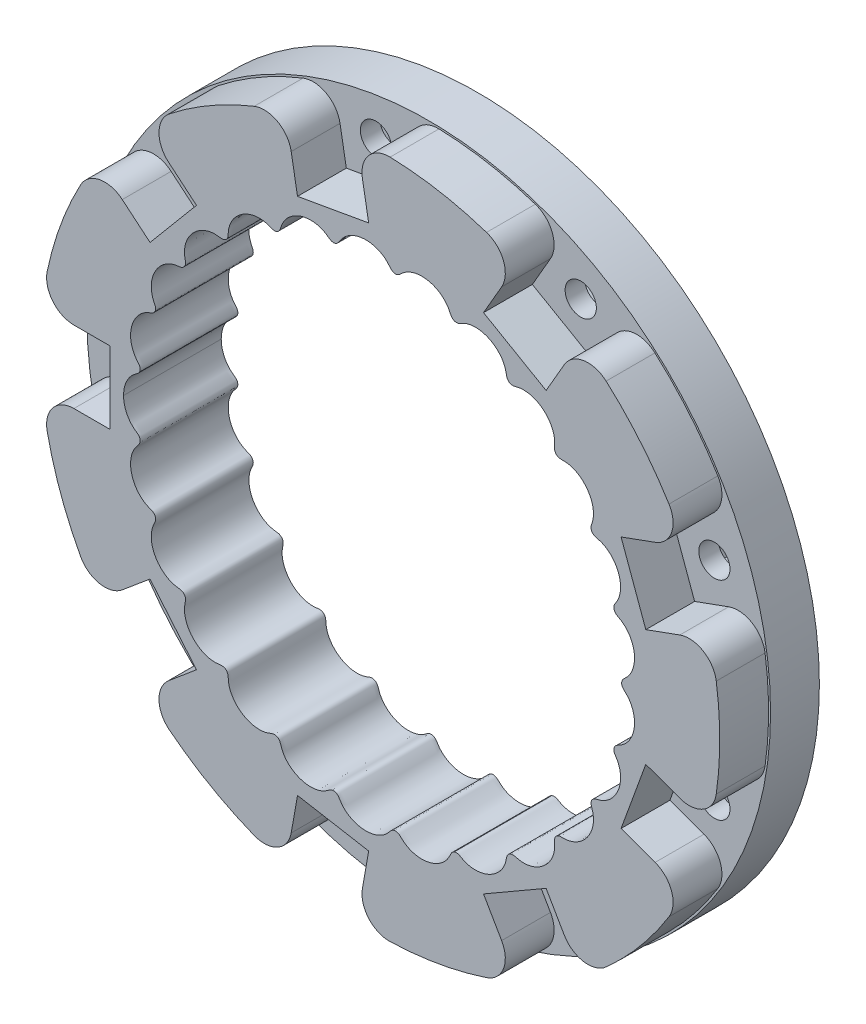
SolidWorks part; units mm, degrees
ref_plane "Plan de face" through (0, 0, 0) normal (0, 0, 1) x (1, 0, 0)
ref_plane "Plan de dessus" through (0, 0, 0) normal (0, 1, 0) x (1, 0, 0)
ref_plane "Plan de droite" through (0, 0, 0) normal (1, 0, 0) x (0, 0, -1)
sketch "Esquisse1" plane through (0, 0, 0) normal (0, 0, 1) x (1, 0, 0)
  line L0 (-1000, 0) -> (49000, 0) construction
  circle A1 centre (0, 0) radius 35
  spline S0 degree 4 poles (24.1426, 6.7991) (24.1177, 6.7609) (24.0692, 6.6836) (24.0004, 6.5645) (23.9483, 6.387) (23.9505, 6.1855) (24.0272, 5.9803) (24.1778, 5.8151) (24.3705, 5.7045) (24.5983, 5.5844) (24.8479, 5.4264) (25.1139, 5.2067) (25.3819, 4.9129) (25.6102, 4.583) (25.7961, 4.2235) (25.9371, 3.8403) (26.0305, 3.4429) (26.0756, 3.0373) (26.0716, 2.6291) (26.0179, 2.2244) (25.9151, 1.834) (25.7643, 1.4641) (25.5917, 1.1641) (25.4167, 0.9296) (25.2526, 0.7496) (25.1124, 0.6144) (24.9828, 0.4987) (24.8797, 0.3844) (24.8179, 0.2829) (24.7848, 0.2051) (24.7673, 0.1461) (24.7588, 0.1043) (24.7529, 0.0597) (24.7496, 0.0145) (24.7496, -0.0147) (24.7529, -0.06) (24.7589, -0.1048) (24.7675, -0.1468) (24.7852, -0.2061) (24.8185, -0.2842) (24.8808, -0.3859) (24.9847, -0.5005) (25.1148, -0.6166) (25.2554, -0.7525) (25.4198, -0.9333) (25.595, -1.1691) (25.7689, -1.4729) (25.9207, -1.8497) (26.0235, -2.2499) (26.0747, -2.6669) (26.0733, -3.0863) (26.0204, -3.5015) (25.917, -3.9063) (25.7644, -4.2943) (25.5662, -4.6548) (25.3259, -4.9815) (25.0816, -5.2331) (24.8519, -5.4186) (24.6671, -5.5402) (24.5395, -5.6139) (24.4102, -5.6846) (24.274, -5.758) (24.12, -5.8678) (23.9899, -6.0503) (23.9364, -6.2751) (23.9692, -6.4958) (24.0654, -6.6843) (24.1784, -6.8519) (24.2801, -7.019) (24.3936, -7.2353) (24.5034, -7.5077) (24.5951, -7.8454) (24.647, -8.2482) (24.6457, -8.6612) (24.576, -9.1855) (24.4176, -9.6961) (24.1747, -10.1766) (23.852, -10.6101) (23.5588, -10.9098) (23.241, -11.1578) (22.9466, -11.3291) (22.6921, -11.4408) (22.4727, -11.5135) (22.2939, -11.5615) (22.1013, -11.606) (21.9021, -11.6816) (21.7285, -11.8281) (21.6209, -12.0388) (21.6016, -12.2637) (21.6505, -12.4693) (21.7183, -12.6598) (21.7746, -12.8471) (21.8297, -13.085) (21.8672, -13.3762) (21.8707, -13.726) (21.8195, -14.1287) (21.7142, -14.528) (21.5148, -15.0178) (21.2331, -15.4721) (20.8771, -15.876) (20.4557, -16.2144) (20.0964, -16.4307) (19.7262, -16.5906) (19.3981, -16.6821) (19.1236, -16.7259) (18.8929, -16.7409) (18.7078, -16.7424) (18.5101, -16.7378) (18.2984, -16.7644) (18.0955, -16.8669) (17.9421, -17.0472) (17.8714, -17.2614) (17.8702, -17.4725) (17.8883, -17.6738) (17.8957, -17.8692) (17.8889, -18.1133) (17.8517, -18.4044) (17.7668, -18.7438) (17.6158, -19.1205) (17.4134, -19.4803) (17.1623, -19.8168) (16.8685, -20.1221) (16.5358, -20.3908) (16.1684, -20.6173) (15.771, -20.7957) (15.3688, -20.9145) (14.9702, -20.976) (14.6296, -20.9817) (14.3529, -20.9549) (14.1259, -20.9112) (13.9464, -20.866) (13.7558, -20.8128) (13.5435, -20.7889) (13.3222, -20.8417) (13.1314, -20.9817) (13.013, -21.1736) (12.9618, -21.3782) (12.9291, -21.5776) (12.887, -21.7685) (12.8188, -22.0029) (12.7093, -22.2752) (12.5416, -22.5821) (12.3006, -22.9086) (12.0142, -23.2057) (11.6866, -23.4682) (11.3255, -23.6897) (10.9359, -23.8661) (10.5233, -23.9928) (10.0937, -24.0655) (9.6744, -24.0792) (9.2731, -24.0382) (8.942, -23.9578) (8.6811, -23.862) (8.4724, -23.7624) (8.31, -23.6735) (8.1383, -23.575) (7.9372, -23.5018) (7.7049, -23.5021) (7.4781, -23.6007) (7.3169, -23.7729) (7.2208, -23.9706) (7.1156, -24.2034) (6.9743, -24.4604) (6.773, -24.7375) (6.4979, -25.0224) (6.1834, -25.2709) (5.8357, -25.4797) (5.4603, -25.6452) (5.0615, -25.7656) (4.6447, -25.8371) (4.2157, -25.8559) (3.7816, -25.8181) (3.3723, -25.7258) (2.9942, -25.5849) (2.6941, -25.4236) (2.4656, -25.2649) (2.2891, -25.1158) (2.1537, -24.9891) (2.0123, -24.8511) (1.8324, -24.7331) (1.553, -24.6659) (1.2621, -24.7546) (1.0754, -24.9576) (0.8891, -25.1941) (0.6967, -25.4018) (0.4476, -25.6153) (0.1257, -25.8218) (-0.2246, -25.9871) (-0.599, -26.1091) (-0.9909, -26.1853) (-1.3919, -26.2146) (-1.7962, -26.1958) (-2.1981, -26.1285) (-2.5915, -26.0119) (-2.9628, -25.849) (-3.3062, -25.6424) (-3.6154, -25.3948) (-3.8503, -25.1456) (-4.0231, -24.9087) (-4.157, -24.6911) (-4.2763, -24.5066) (-4.4563, -24.3545) (-4.6931, -24.2829) (-4.9238, -24.3097) (-5.115, -24.4061) (-5.2732, -24.5252) (-5.423, -24.6339) (-5.6174, -24.7592) (-5.864, -24.8876) (-6.1822, -25.0094) (-6.5751, -25.1011) (-6.9928, -25.1407) (-7.4281, -25.1231) (-7.8512, -25.0501) (-8.2556, -24.9263) (-8.636, -24.7563) (-8.9874, -24.5444) (-9.3058, -24.2932) (-9.5861, -24.0067) (-9.8229, -23.6892) (-9.9872, -23.3887) (-10.0948, -23.1158) (-10.1696, -22.8715) (-10.2411, -22.6635) (-10.3812, -22.4737) (-10.595, -22.3493) (-10.8256, -22.322) (-11.0338, -22.3709) (-11.2164, -22.4474) (-11.3887, -22.5149) (-11.6084, -22.5872) (-11.8793, -22.649) (-12.2179, -22.6866) (-12.6212, -22.6763) (-13.0353, -22.6095) (-13.4521, -22.4829) (-13.8453, -22.3049) (-14.2094, -22.0805) (-14.5395, -21.815) (-14.8313, -21.5131) (-15.0777, -21.1819) (-15.2753, -20.8275) (-15.4026, -20.5017) (-15.4765, -20.2177) (-15.5143, -19.9765) (-15.5318, -19.7817) (-15.5392, -19.5798) (-15.5656, -19.3704) (-15.6608, -19.166) (-15.8341, -19.0047) (-16.0476, -18.9266) (-16.2611, -18.9252) (-16.4568, -18.9543) (-16.6405, -18.9763) (-16.8713, -18.9908) (-17.1491, -18.9822) (-17.4862, -18.9332) (-17.8737, -18.8216) (-18.2576, -18.6527) (-18.6291, -18.4253) (-18.9648, -18.1541) (-19.2607, -17.8454) (-19.5135, -17.5053) (-19.7199, -17.1396) (-19.875, -16.7569) (-19.9769, -16.364) (-20.018, -16.0166) (-20.0178, -15.7231) (-19.9934, -15.4801) (-19.9613, -15.2872) (-19.9181, -15.0898) (-19.894, -14.8799) (-19.9394, -14.6589) (-20.0707, -14.462) (-20.2602, -14.3367) (-20.4672, -14.2852) (-20.6639, -14.2651) (-20.8473, -14.2402) (-21.0742, -14.196) (-21.3408, -14.1175) (-21.6546, -13.985) (-22.0015, -13.7794) (-22.3304, -13.5193) (-22.7055, -13.1302) (-23.0074, -12.6844) (-23.2291, -12.1981) (-23.3648, -11.6869) (-23.4186, -11.2774) (-23.4182, -10.8714) (-23.3703, -10.5248) (-23.296, -10.2407) (-23.211, -10.0117) (-23.1314, -9.8331) (-23.0402, -9.6526) (-22.9672, -9.4541) (-22.9601, -9.2287) (-23.0424, -9.0072) (-23.1982, -8.8407) (-23.3889, -8.7414) (-23.5777, -8.6723) (-23.7531, -8.5999) (-23.9662, -8.4963) (-24.2093, -8.3477) (-24.4803, -8.1356) (-24.7613, -7.8463) (-25.0085, -7.5133) (-25.2666, -7.049) (-25.4429, -6.5476) (-25.5339, -6.0256) (-25.5366, -5.4989) (-25.4855, -5.0889) (-25.3828, -4.696) (-25.2489, -4.3726) (-25.1052, -4.1164) (-24.9652, -3.9162) (-24.8431, -3.7634) (-24.7098, -3.6112) (-24.5919, -3.4354) (-24.5338, -3.2206) (-24.5604, -2.9926) (-24.6667, -2.797) (-24.8227, -2.6537) (-24.9897, -2.5393) (-25.1463, -2.4221) (-25.3325, -2.2638) (-25.5023, -2.0873) (-25.6545, -1.8958) (-25.7905, -1.6883) (-25.89, -1.512) (-25.979, -1.3255) (-26.0566, -1.1315) (-26.1214, -0.9307) (-26.1732, -0.7298) (-26.2073, -0.5457) (-26.2284, -0.3959) (-26.2405, -0.2557) (-26.247, -0.1691) (-26.2503, -0.0328) (-26.2503, 0.0323) (-26.2471, 0.1679) (-26.2407, 0.2542) (-26.2286, 0.3933) (-26.2078, 0.5423) (-26.1742, 0.7251) (-26.123, 0.925) (-26.0591, 1.1245) (-25.9824, 1.3176) (-25.8737, 1.547) (-25.7224, 1.8046) (-25.5451, 2.0414) (-25.3437, 2.2529) (-25.1596, 2.4115) (-25.0044, 2.5289) (-24.8386, 2.6423) (-24.6804, 2.7808) (-24.5546, 2.9935) (-24.5303, 3.2355) (-24.6, 3.4498) (-24.7118, 3.6094) (-24.804, 3.7191) (-24.9086, 3.8447) (-25.0204, 3.9911) (-25.1376, 4.1713) (-25.2521, 4.3886) (-25.3469, 4.6153) (-25.4409, 4.9075) (-25.515, 5.269) (-25.5464, 5.6988) (-25.509, 6.1899) (-25.401, 6.6704) (-25.2688, 7.0153) (-25.1588, 7.235) (-25.0985, 7.3418) knots 0 0 0 0 0 0.001685 0.003369 0.005054 0.006738 0.009006 0.011274 0.013086 0.014899 0.018524 0.022149 0.025774 0.029532 0.03329 0.037047 0.040805 0.044562 0.048319 0.052076 0.055834 0.059425 0.063017 0.064813 0.066609 0.068405 0.070201 0.071231 0.072261 0.072776 0.073291 0.073548 0.073806 0.074321 0.074838 0.075097 0.075356 0.075873 0.07639 0.077425 0.07846 0.080263 0.082066 0.083868 0.085671 0.089277 0.092883 0.09675 0.100617 0.104484 0.108351 0.112188 0.116026 0.119864 0.123701 0.127327 0.130952 0.132764 0.134577 0.135483 0.13639 0.138202 0.140296 0.142389 0.144459 0.146528 0.148331 0.150133 0.151935 0.153737 0.157342 0.160946 0.164812 0.168678 0.172544 0.180416 0.184421 0.188427 0.192432 0.195844 0.199256 0.200962 0.202668 0.204374 0.20608 0.208269 0.210458 0.212527 0.214596 0.216398 0.2182 0.220001 0.221803 0.225407 0.22901 0.232875 0.23674 0.240605 0.248477 0.252483 0.256489 0.260496 0.263908 0.26732 0.269026 0.270732 0.272438 0.274144 0.276335 0.278527 0.280595 0.282663 0.284464 0.286266 0.288067 0.289868 0.293471 0.297074 0.300938 0.304802 0.308666 0.31253 0.316537 0.320545 0.324552 0.328559 0.331971 0.335384 0.33709 0.338796 0.340502 0.342208 0.344401 0.346595 0.348662 0.350729 0.35253 0.354331 0.356132 0.357933 0.361536 0.365138 0.369001 0.372864 0.376727 0.38059 0.384598 0.388606 0.392614 0.396623 0.400035 0.403448 0.405154 0.40686 0.408567 0.410273 0.412468 0.414663 0.416905 0.419148 0.420948 0.422747 0.426346 0.429946 0.433545 0.437321 0.441097 0.444873 0.44865 0.452659 0.456668 0.460677 0.464686 0.468099 0.471512 0.473218 0.474925 0.476631 0.478338 0.480534 0.48273 0.48702 0.488749 0.490478 0.493937 0.497395 0.500854 0.50453 0.508207 0.511883 0.515559 0.519335 0.523111 0.526887 0.530662 0.534262 0.537861 0.54146 0.543259 0.545059 0.547301 0.549542 0.551738 0.553933 0.55564 0.557346 0.559053 0.560759 0.564172 0.567585 0.571593 0.575602 0.57961 0.583619 0.587396 0.591172 0.594949 0.598726 0.602325 0.605924 0.609523 0.611323 0.613123 0.615366 0.61761 0.619804 0.621998 0.623704 0.625411 0.627117 0.628823 0.632235 0.635648 0.639656 0.643663 0.647671 0.651679 0.655542 0.659406 0.663269 0.667133 0.670735 0.674338 0.676139 0.67794 0.679742 0.681543 0.68361 0.685678 0.68787 0.690063 0.691769 0.693475 0.695181 0.696887 0.700299 0.703711 0.707718 0.711725 0.715732 0.719739 0.723603 0.727468 0.731332 0.735197 0.7388 0.742403 0.744204 0.746006 0.747808 0.749609 0.751678 0.753746 0.755937 0.758127 0.759833 0.761539 0.763245 0.764951 0.768363 0.771775 0.775781 0.779787 0.783793 0.791664 0.795529 0.799395 0.80326 0.806864 0.810468 0.81227 0.814073 0.815875 0.817677 0.819746 0.821815 0.823999 0.826183 0.827931 0.82968 0.831429 0.833177 0.836675 0.840172 0.844094 0.848015 0.851937 0.859725 0.863591 0.867458 0.871324 0.874929 0.878534 0.880337 0.882139 0.883942 0.885745 0.887814 0.889884 0.891953 0.894023 0.895826 0.897629 0.899432 0.901235 0.904841 0.906644 0.908448 0.910381 0.912315 0.914249 0.916183 0.918117 0.92005 0.921017 0.921984 0.922951 0.923918 0.924879 0.925839 0.9268 0.927761 0.929682 0.931604 0.933525 0.935447 0.937368 0.93929 0.942875 0.94646 0.948253 0.950045 0.951838 0.95363 0.955683 0.957735 0.960756 0.962266 0.963777 0.964909 0.96604 0.968304 0.970568 0.972832 0.975095 0.977359 0.981887 0.986415 0.990943 0.995472 1 1 1 1 1 construction
  spline S1 degree 4 poles (24.75, 0) (24.75, -0.0119) (24.7507, -0.0298) (24.7529, -0.06) (24.7589, -0.1048) (24.7675, -0.1468) (24.7852, -0.2061) (24.8185, -0.2842) (24.8808, -0.3859) (24.9847, -0.5005) (25.1148, -0.6166) (25.2554, -0.7525) (25.4198, -0.9333) (25.595, -1.1691) (25.7689, -1.4729) (25.9207, -1.8497) (26.0235, -2.2499) (26.0747, -2.6669) (26.0733, -3.0863) (26.0204, -3.5015) (25.917, -3.9063) (25.7644, -4.2943) (25.5662, -4.6548) (25.3259, -4.9815) (25.0816, -5.2331) (24.8519, -5.4186) (24.6671, -5.5402) (24.5395, -5.6139) (24.4102, -5.6846) (24.274, -5.758) (24.12, -5.8678) (23.9899, -6.0503) (23.9364, -6.2751) (23.9692, -6.4958) (24.0654, -6.6843) (24.1784, -6.8519) (24.2801, -7.019) (24.3936, -7.2353) (24.5034, -7.5077) (24.5951, -7.8454) (24.647, -8.2482) (24.6457, -8.6612) (24.576, -9.1855) (24.4176, -9.6961) (24.1747, -10.1766) (23.852, -10.6101) (23.5588, -10.9098) (23.241, -11.1578) (22.9466, -11.3291) (22.6921, -11.4408) (22.4727, -11.5135) (22.2939, -11.5615) (22.1013, -11.606) (21.9021, -11.6816) (21.7285, -11.8281) (21.6209, -12.0388) (21.6016, -12.2637) (21.6505, -12.4693) (21.7183, -12.6598) (21.7746, -12.8471) (21.8297, -13.085) (21.8672, -13.3762) (21.8707, -13.726) (21.8195, -14.1287) (21.7142, -14.528) (21.5148, -15.0178) (21.2331, -15.4721) (20.8771, -15.876) (20.4557, -16.2144) (20.0964, -16.4307) (19.7262, -16.5906) (19.3981, -16.6821) (19.1236, -16.7259) (18.8929, -16.7409) (18.7078, -16.7424) (18.5101, -16.7378) (18.2984, -16.7644) (18.0955, -16.8669) (17.9421, -17.0472) (17.8714, -17.2614) (17.8702, -17.4725) (17.8883, -17.6738) (17.8957, -17.8692) (17.8889, -18.1133) (17.8517, -18.4044) (17.7668, -18.7438) (17.6158, -19.1205) (17.4134, -19.4803) (17.1623, -19.8168) (16.8685, -20.1221) (16.5358, -20.3908) (16.1684, -20.6173) (15.771, -20.7957) (15.3688, -20.9145) (14.9702, -20.976) (14.6296, -20.9817) (14.3529, -20.9549) (14.1259, -20.9112) (13.9464, -20.866) (13.7558, -20.8128) (13.5435, -20.7889) (13.3222, -20.8417) (13.1314, -20.9817) (13.013, -21.1736) (12.9618, -21.3782) (12.9291, -21.5776) (12.887, -21.7685) (12.8188, -22.0029) (12.7093, -22.2752) (12.5416, -22.5821) (12.3006, -22.9086) (12.0142, -23.2057) (11.6866, -23.4682) (11.3255, -23.6897) (10.9359, -23.8661) (10.5233, -23.9928) (10.0937, -24.0655) (9.6744, -24.0792) (9.2731, -24.0382) (8.942, -23.9578) (8.6811, -23.862) (8.4724, -23.7624) (8.31, -23.6735) (8.1383, -23.575) (7.9372, -23.5018) (7.7049, -23.5021) (7.4781, -23.6007) (7.3169, -23.7729) (7.2208, -23.9706) (7.1156, -24.2034) (6.9743, -24.4604) (6.773, -24.7375) (6.4979, -25.0224) (6.1834, -25.2709) (5.8357, -25.4797) (5.4603, -25.6452) (5.0615, -25.7656) (4.6447, -25.8371) (4.2157, -25.8559) (3.7816, -25.8181) (3.3723, -25.7258) (2.9942, -25.5849) (2.6941, -25.4236) (2.4656, -25.2649) (2.2891, -25.1158) (2.1537, -24.9891) (2.0123, -24.8511) (1.8324, -24.7331) (1.553, -24.6659) (1.2621, -24.7546) (1.0754, -24.9576) (0.8891, -25.1941) (0.6967, -25.4018) (0.4476, -25.6153) (0.1257, -25.8218) (-0.2246, -25.9871) (-0.599, -26.1091) (-0.9909, -26.1853) (-1.3919, -26.2146) (-1.7962, -26.1958) (-2.1981, -26.1285) (-2.5915, -26.0119) (-2.9628, -25.849) (-3.3062, -25.6424) (-3.6154, -25.3948) (-3.8503, -25.1456) (-4.0231, -24.9087) (-4.157, -24.6911) (-4.2763, -24.5066) (-4.4563, -24.3545) (-4.6931, -24.2829) (-4.9238, -24.3097) (-5.115, -24.4061) (-5.2732, -24.5252) (-5.423, -24.6339) (-5.6174, -24.7592) (-5.864, -24.8876) (-6.1822, -25.0094) (-6.5751, -25.1011) (-6.9928, -25.1407) (-7.4281, -25.1231) (-7.8512, -25.0501) (-8.2556, -24.9263) (-8.636, -24.7563) (-8.9874, -24.5444) (-9.3058, -24.2932) (-9.5861, -24.0067) (-9.8229, -23.6892) (-9.9872, -23.3887) (-10.0948, -23.1158) (-10.1696, -22.8715) (-10.2411, -22.6635) (-10.3812, -22.4737) (-10.595, -22.3493) (-10.8256, -22.322) (-11.0338, -22.3709) (-11.2164, -22.4474) (-11.3887, -22.5149) (-11.6084, -22.5872) (-11.8793, -22.649) (-12.2179, -22.6866) (-12.6212, -22.6763) (-13.0353, -22.6095) (-13.4521, -22.4829) (-13.8453, -22.3049) (-14.2094, -22.0805) (-14.5395, -21.815) (-14.8313, -21.5131) (-15.0777, -21.1819) (-15.2753, -20.8275) (-15.4026, -20.5017) (-15.4765, -20.2177) (-15.5143, -19.9765) (-15.5318, -19.7817) (-15.5392, -19.5798) (-15.5656, -19.3704) (-15.6608, -19.166) (-15.8341, -19.0047) (-16.0476, -18.9266) (-16.2611, -18.9252) (-16.4568, -18.9543) (-16.6405, -18.9763) (-16.8713, -18.9908) (-17.1491, -18.9822) (-17.4862, -18.9332) (-17.8737, -18.8216) (-18.2576, -18.6527) (-18.6291, -18.4253) (-18.9648, -18.1541) (-19.2607, -17.8454) (-19.5135, -17.5053) (-19.7199, -17.1396) (-19.875, -16.7569) (-19.9769, -16.364) (-20.018, -16.0166) (-20.0178, -15.7231) (-19.9934, -15.4801) (-19.9613, -15.2872) (-19.9181, -15.0898) (-19.894, -14.8799) (-19.9394, -14.6589) (-20.0707, -14.462) (-20.2602, -14.3367) (-20.4672, -14.2852) (-20.6639, -14.2651) (-20.8473, -14.2402) (-21.0742, -14.196) (-21.3408, -14.1175) (-21.6546, -13.985) (-22.0015, -13.7794) (-22.3304, -13.5193) (-22.7055, -13.1302) (-23.0074, -12.6844) (-23.2291, -12.1981) (-23.3648, -11.6869) (-23.4186, -11.2774) (-23.4182, -10.8714) (-23.3703, -10.5248) (-23.296, -10.2407) (-23.211, -10.0117) (-23.1314, -9.8331) (-23.0402, -9.6526) (-22.9672, -9.4541) (-22.9601, -9.2287) (-23.0424, -9.0072) (-23.1982, -8.8407) (-23.3889, -8.7414) (-23.5777, -8.6723) (-23.7531, -8.5999) (-23.9662, -8.4963) (-24.2093, -8.3477) (-24.4803, -8.1356) (-24.7613, -7.8463) (-25.0085, -7.5133) (-25.2666, -7.049) (-25.4429, -6.5476) (-25.5339, -6.0256) (-25.5366, -5.4989) (-25.4855, -5.0889) (-25.3828, -4.696) (-25.2489, -4.3726) (-25.1052, -4.1164) (-24.9652, -3.9162) (-24.8431, -3.7634) (-24.7098, -3.6112) (-24.5919, -3.4354) (-24.5338, -3.2206) (-24.5604, -2.9926) (-24.6667, -2.797) (-24.8227, -2.6537) (-24.9897, -2.5393) (-25.1463, -2.4221) (-25.3325, -2.2638) (-25.5023, -2.0873) (-25.6545, -1.8958) (-25.7905, -1.6883) (-25.89, -1.512) (-25.979, -1.3255) (-26.0566, -1.1315) (-26.1214, -0.9307) (-26.1732, -0.7298) (-26.2073, -0.5457) (-26.2284, -0.3959) (-26.2405, -0.2557) (-26.247, -0.1691) (-26.2495, -0.0667) (-26.25, -0.0223) (-26.25, 0) knots 0.074321 0.074321 0.074321 0.074321 0.074321 0.074838 0.075097 0.075356 0.075873 0.07639 0.077425 0.07846 0.080263 0.082066 0.083868 0.085671 0.089277 0.092883 0.09675 0.100617 0.104484 0.108351 0.112188 0.116026 0.119864 0.123701 0.127327 0.130952 0.132764 0.134577 0.135483 0.13639 0.138202 0.140296 0.142389 0.144459 0.146528 0.148331 0.150133 0.151935 0.153737 0.157342 0.160946 0.164812 0.168678 0.172544 0.180416 0.184421 0.188427 0.192432 0.195844 0.199256 0.200962 0.202668 0.204374 0.20608 0.208269 0.210458 0.212527 0.214596 0.216398 0.2182 0.220001 0.221803 0.225407 0.22901 0.232875 0.23674 0.240605 0.248477 0.252483 0.256489 0.260496 0.263908 0.26732 0.269026 0.270732 0.272438 0.274144 0.276335 0.278527 0.280595 0.282663 0.284464 0.286266 0.288067 0.289868 0.293471 0.297074 0.300938 0.304802 0.308666 0.31253 0.316537 0.320545 0.324552 0.328559 0.331971 0.335384 0.33709 0.338796 0.340502 0.342208 0.344401 0.346595 0.348662 0.350729 0.35253 0.354331 0.356132 0.357933 0.361536 0.365138 0.369001 0.372864 0.376727 0.38059 0.384598 0.388606 0.392614 0.396623 0.400035 0.403448 0.405154 0.40686 0.408567 0.410273 0.412468 0.414663 0.416905 0.419148 0.420948 0.422747 0.426346 0.429946 0.433545 0.437321 0.441097 0.444873 0.44865 0.452659 0.456668 0.460677 0.464686 0.468099 0.471512 0.473218 0.474925 0.476631 0.478338 0.480534 0.48273 0.48702 0.488749 0.490478 0.493937 0.497395 0.500854 0.50453 0.508207 0.511883 0.515559 0.519335 0.523111 0.526887 0.530662 0.534262 0.537861 0.54146 0.543259 0.545059 0.547301 0.549542 0.551738 0.553933 0.55564 0.557346 0.559053 0.560759 0.564172 0.567585 0.571593 0.575602 0.57961 0.583619 0.587396 0.591172 0.594949 0.598726 0.602325 0.605924 0.609523 0.611323 0.613123 0.615366 0.61761 0.619804 0.621998 0.623704 0.625411 0.627117 0.628823 0.632235 0.635648 0.639656 0.643663 0.647671 0.651679 0.655542 0.659406 0.663269 0.667133 0.670735 0.674338 0.676139 0.67794 0.679742 0.681543 0.68361 0.685678 0.68787 0.690063 0.691769 0.693475 0.695181 0.696887 0.700299 0.703711 0.707718 0.711725 0.715732 0.719739 0.723603 0.727468 0.731332 0.735197 0.7388 0.742403 0.744204 0.746006 0.747808 0.749609 0.751678 0.753746 0.755937 0.758127 0.759833 0.761539 0.763245 0.764951 0.768363 0.771775 0.775781 0.779787 0.783793 0.791664 0.795529 0.799395 0.80326 0.806864 0.810468 0.81227 0.814073 0.815875 0.817677 0.819746 0.821815 0.823999 0.826183 0.827931 0.82968 0.831429 0.833177 0.836675 0.840172 0.844094 0.848015 0.851937 0.859725 0.863591 0.867458 0.871324 0.874929 0.878534 0.880337 0.882139 0.883942 0.885745 0.887814 0.889884 0.891953 0.894023 0.895826 0.897629 0.899432 0.901235 0.904841 0.906644 0.908448 0.910381 0.912315 0.914249 0.916183 0.918117 0.92005 0.921017 0.921984 0.922951 0.923918 0.923918 0.923918 0.923918 0.923918
  spline S2 degree 4 poles (24.75, 0) (24.75, 0.0119) (24.7507, 0.0298) (24.7529, 0.06) (24.7589, 0.1048) (24.7675, 0.1468) (24.7852, 0.2061) (24.8185, 0.2842) (24.8808, 0.3859) (24.9847, 0.5005) (25.1148, 0.6166) (25.2554, 0.7525) (25.4198, 0.9333) (25.595, 1.1691) (25.7689, 1.4729) (25.9207, 1.8497) (26.0235, 2.2499) (26.0747, 2.6669) (26.0733, 3.0863) (26.0204, 3.5015) (25.917, 3.9063) (25.7644, 4.2943) (25.5662, 4.6548) (25.3259, 4.9815) (25.0816, 5.2331) (24.8519, 5.4186) (24.6671, 5.5402) (24.5395, 5.6139) (24.4102, 5.6846) (24.274, 5.758) (24.12, 5.8678) (23.9899, 6.0503) (23.9364, 6.2751) (23.9692, 6.4958) (24.0654, 6.6843) (24.1784, 6.8519) (24.2801, 7.019) (24.3936, 7.2353) (24.5034, 7.5077) (24.5951, 7.8454) (24.647, 8.2482) (24.6457, 8.6612) (24.576, 9.1855) (24.4176, 9.6961) (24.1747, 10.1766) (23.852, 10.6101) (23.5588, 10.9098) (23.241, 11.1578) (22.9466, 11.3291) (22.6921, 11.4408) (22.4727, 11.5135) (22.2939, 11.5615) (22.1013, 11.606) (21.9021, 11.6816) (21.7285, 11.8281) (21.6209, 12.0388) (21.6016, 12.2637) (21.6505, 12.4693) (21.7183, 12.6598) (21.7746, 12.8471) (21.8297, 13.085) (21.8672, 13.3762) (21.8707, 13.726) (21.8195, 14.1287) (21.7142, 14.528) (21.5148, 15.0178) (21.2331, 15.4721) (20.8771, 15.876) (20.4557, 16.2144) (20.0964, 16.4307) (19.7262, 16.5906) (19.3981, 16.6821) (19.1236, 16.7259) (18.8929, 16.7409) (18.7078, 16.7424) (18.5101, 16.7378) (18.2984, 16.7644) (18.0955, 16.8669) (17.9421, 17.0472) (17.8714, 17.2614) (17.8702, 17.4725) (17.8883, 17.6738) (17.8957, 17.8692) (17.8889, 18.1133) (17.8517, 18.4044) (17.7668, 18.7438) (17.6158, 19.1205) (17.4134, 19.4803) (17.1623, 19.8168) (16.8685, 20.1221) (16.5358, 20.3908) (16.1684, 20.6173) (15.771, 20.7957) (15.3688, 20.9145) (14.9702, 20.976) (14.6296, 20.9817) (14.3529, 20.9549) (14.1259, 20.9112) (13.9464, 20.866) (13.7558, 20.8128) (13.5435, 20.7889) (13.3222, 20.8417) (13.1314, 20.9817) (13.013, 21.1736) (12.9618, 21.3782) (12.9291, 21.5776) (12.887, 21.7685) (12.8188, 22.0029) (12.7093, 22.2752) (12.5416, 22.5821) (12.3006, 22.9086) (12.0142, 23.2057) (11.6866, 23.4682) (11.3255, 23.6897) (10.9359, 23.8661) (10.5233, 23.9928) (10.0937, 24.0655) (9.6744, 24.0792) (9.2731, 24.0382) (8.942, 23.9578) (8.6811, 23.862) (8.4724, 23.7624) (8.31, 23.6735) (8.1383, 23.575) (7.9372, 23.5018) (7.7049, 23.5021) (7.4781, 23.6007) (7.3169, 23.7729) (7.2208, 23.9706) (7.1156, 24.2034) (6.9743, 24.4604) (6.773, 24.7375) (6.4979, 25.0224) (6.1834, 25.2709) (5.8357, 25.4797) (5.4603, 25.6452) (5.0615, 25.7656) (4.6447, 25.8371) (4.2157, 25.8559) (3.7816, 25.8181) (3.3723, 25.7258) (2.9942, 25.5849) (2.6941, 25.4236) (2.4656, 25.2649) (2.2891, 25.1158) (2.1537, 24.9891) (2.0123, 24.8511) (1.8324, 24.7331) (1.553, 24.6659) (1.2621, 24.7546) (1.0754, 24.9576) (0.8891, 25.1941) (0.6967, 25.4018) (0.4476, 25.6153) (0.1257, 25.8218) (-0.2246, 25.9871) (-0.599, 26.1091) (-0.9909, 26.1853) (-1.3919, 26.2146) (-1.7962, 26.1958) (-2.1981, 26.1285) (-2.5915, 26.0119) (-2.9628, 25.849) (-3.3062, 25.6424) (-3.6154, 25.3948) (-3.8503, 25.1456) (-4.0231, 24.9087) (-4.157, 24.6911) (-4.2763, 24.5066) (-4.4563, 24.3545) (-4.6931, 24.2829) (-4.9238, 24.3097) (-5.115, 24.4061) (-5.2732, 24.5252) (-5.423, 24.6339) (-5.6174, 24.7592) (-5.864, 24.8876) (-6.1822, 25.0094) (-6.5751, 25.1011) (-6.9928, 25.1407) (-7.4281, 25.1231) (-7.8512, 25.0501) (-8.2556, 24.9263) (-8.636, 24.7563) (-8.9874, 24.5444) (-9.3058, 24.2932) (-9.5861, 24.0067) (-9.8229, 23.6892) (-9.9872, 23.3887) (-10.0948, 23.1158) (-10.1696, 22.8715) (-10.2411, 22.6635) (-10.3812, 22.4737) (-10.595, 22.3493) (-10.8256, 22.322) (-11.0338, 22.3709) (-11.2164, 22.4474) (-11.3887, 22.5149) (-11.6084, 22.5872) (-11.8793, 22.649) (-12.2179, 22.6866) (-12.6212, 22.6763) (-13.0353, 22.6095) (-13.4521, 22.4829) (-13.8453, 22.3049) (-14.2094, 22.0805) (-14.5395, 21.815) (-14.8313, 21.5131) (-15.0777, 21.1819) (-15.2753, 20.8275) (-15.4026, 20.5017) (-15.4765, 20.2177) (-15.5143, 19.9765) (-15.5318, 19.7817) (-15.5392, 19.5798) (-15.5656, 19.3704) (-15.6608, 19.166) (-15.8341, 19.0047) (-16.0476, 18.9266) (-16.2611, 18.9252) (-16.4568, 18.9543) (-16.6405, 18.9763) (-16.8713, 18.9908) (-17.1491, 18.9822) (-17.4862, 18.9332) (-17.8737, 18.8216) (-18.2576, 18.6527) (-18.6291, 18.4253) (-18.9648, 18.1541) (-19.2607, 17.8454) (-19.5135, 17.5053) (-19.7199, 17.1396) (-19.875, 16.7569) (-19.9769, 16.364) (-20.018, 16.0166) (-20.0178, 15.7231) (-19.9934, 15.4801) (-19.9613, 15.2872) (-19.9181, 15.0898) (-19.894, 14.8799) (-19.9394, 14.6589) (-20.0707, 14.462) (-20.2602, 14.3367) (-20.4672, 14.2852) (-20.6639, 14.2651) (-20.8473, 14.2402) (-21.0742, 14.196) (-21.3408, 14.1175) (-21.6546, 13.985) (-22.0015, 13.7794) (-22.3304, 13.5193) (-22.7055, 13.1302) (-23.0074, 12.6844) (-23.2291, 12.1981) (-23.3648, 11.6869) (-23.4186, 11.2774) (-23.4182, 10.8714) (-23.3703, 10.5248) (-23.296, 10.2407) (-23.211, 10.0117) (-23.1314, 9.8331) (-23.0402, 9.6526) (-22.9672, 9.4541) (-22.9601, 9.2287) (-23.0424, 9.0072) (-23.1982, 8.8407) (-23.3889, 8.7414) (-23.5777, 8.6723) (-23.7531, 8.5999) (-23.9662, 8.4963) (-24.2093, 8.3477) (-24.4803, 8.1356) (-24.7613, 7.8463) (-25.0085, 7.5133) (-25.2666, 7.049) (-25.4429, 6.5476) (-25.5339, 6.0256) (-25.5366, 5.4989) (-25.4855, 5.0889) (-25.3828, 4.696) (-25.2489, 4.3726) (-25.1052, 4.1164) (-24.9652, 3.9162) (-24.8431, 3.7634) (-24.7098, 3.6112) (-24.5919, 3.4354) (-24.5338, 3.2206) (-24.5604, 2.9926) (-24.6667, 2.797) (-24.8227, 2.6537) (-24.9897, 2.5393) (-25.1463, 2.4221) (-25.3325, 2.2638) (-25.5023, 2.0873) (-25.6545, 1.8958) (-25.7905, 1.6883) (-25.89, 1.512) (-25.979, 1.3255) (-26.0566, 1.1315) (-26.1214, 0.9307) (-26.1732, 0.7298) (-26.2073, 0.5457) (-26.2284, 0.3959) (-26.2405, 0.2557) (-26.247, 0.1691) (-26.2495, 0.0667) (-26.25, 0.0223) (-26.25, 0) knots 0.074321 0.074321 0.074321 0.074321 0.074321 0.074838 0.075097 0.075356 0.075873 0.07639 0.077425 0.07846 0.080263 0.082066 0.083868 0.085671 0.089277 0.092883 0.09675 0.100617 0.104484 0.108351 0.112188 0.116026 0.119864 0.123701 0.127327 0.130952 0.132764 0.134577 0.135483 0.13639 0.138202 0.140296 0.142389 0.144459 0.146528 0.148331 0.150133 0.151935 0.153737 0.157342 0.160946 0.164812 0.168678 0.172544 0.180416 0.184421 0.188427 0.192432 0.195844 0.199256 0.200962 0.202668 0.204374 0.20608 0.208269 0.210458 0.212527 0.214596 0.216398 0.2182 0.220001 0.221803 0.225407 0.22901 0.232875 0.23674 0.240605 0.248477 0.252483 0.256489 0.260496 0.263908 0.26732 0.269026 0.270732 0.272438 0.274144 0.276335 0.278527 0.280595 0.282663 0.284464 0.286266 0.288067 0.289868 0.293471 0.297074 0.300938 0.304802 0.308666 0.31253 0.316537 0.320545 0.324552 0.328559 0.331971 0.335384 0.33709 0.338796 0.340502 0.342208 0.344401 0.346595 0.348662 0.350729 0.35253 0.354331 0.356132 0.357933 0.361536 0.365138 0.369001 0.372864 0.376727 0.38059 0.384598 0.388606 0.392614 0.396623 0.400035 0.403448 0.405154 0.40686 0.408567 0.410273 0.412468 0.414663 0.416905 0.419148 0.420948 0.422747 0.426346 0.429946 0.433545 0.437321 0.441097 0.444873 0.44865 0.452659 0.456668 0.460677 0.464686 0.468099 0.471512 0.473218 0.474925 0.476631 0.478338 0.480534 0.48273 0.48702 0.488749 0.490478 0.493937 0.497395 0.500854 0.50453 0.508207 0.511883 0.515559 0.519335 0.523111 0.526887 0.530662 0.534262 0.537861 0.54146 0.543259 0.545059 0.547301 0.549542 0.551738 0.553933 0.55564 0.557346 0.559053 0.560759 0.564172 0.567585 0.571593 0.575602 0.57961 0.583619 0.587396 0.591172 0.594949 0.598726 0.602325 0.605924 0.609523 0.611323 0.613123 0.615366 0.61761 0.619804 0.621998 0.623704 0.625411 0.627117 0.628823 0.632235 0.635648 0.639656 0.643663 0.647671 0.651679 0.655542 0.659406 0.663269 0.667133 0.670735 0.674338 0.676139 0.67794 0.679742 0.681543 0.68361 0.685678 0.68787 0.690063 0.691769 0.693475 0.695181 0.696887 0.700299 0.703711 0.707718 0.711725 0.715732 0.719739 0.723603 0.727468 0.731332 0.735197 0.7388 0.742403 0.744204 0.746006 0.747808 0.749609 0.751678 0.753746 0.755937 0.758127 0.759833 0.761539 0.763245 0.764951 0.768363 0.771775 0.775781 0.779787 0.783793 0.791664 0.795529 0.799395 0.80326 0.806864 0.810468 0.81227 0.814073 0.815875 0.817677 0.819746 0.821815 0.823999 0.826183 0.827931 0.82968 0.831429 0.833177 0.836675 0.840172 0.844094 0.848015 0.851937 0.859725 0.863591 0.867458 0.871324 0.874929 0.878534 0.880337 0.882139 0.883942 0.885745 0.887814 0.889884 0.891953 0.894023 0.895826 0.897629 0.899432 0.901235 0.904841 0.906644 0.908448 0.910381 0.912315 0.914249 0.916183 0.918117 0.92005 0.921017 0.921984 0.922951 0.923918 0.923918 0.923918 0.923918 0.923918
  dimension "D1" = 70
extrude "Boss.-Extru.1" add sketch "Esquisse1" along normal blind 10
sketch "Esquisse2" plane through (0, 0, 10) normal (0, 0, 1) x (1, 0, 0)
  line L0 (-31.3329, -3.7) -> (-27.6246, -3.7)
  line L1 (-31.3329, 3.5) -> (-27.8246, 3.5) construction
  line L3 (-31.3329, -3.5) -> (-27.8246, -3.5) construction
  line L4 (-27.8246, 3.5) -> (-27.8246, -3.5) construction
  line L5 (-34.8246, 3.5) -> (-27.8246, -3.5) construction
  line L6 (-34.8246, -3.5) -> (-27.8246, 3.5) construction
  line L7 (-27.6246, 3.7) -> (-27.6246, -3.7)
  line L8 (-31.3329, 3.7) -> (-27.6246, 3.7)
  line L9 (-21.6241, 22.9748) -> (-18.7833, 20.5911)
  line L10 (-18.7833, 20.5911) -> (-23.54, 14.9224)
  line L11 (-26.3807, 17.306) -> (-23.54, 14.9224)
  line L12 (-1.7971, 31.4994) -> (-1.1532, 27.8474)
  line L13 (-1.1532, 27.8474) -> (-8.4407, 26.5624)
  line L14 (-9.0847, 30.2144) -> (-8.4407, 26.5624)
  line L15 (18.8707, 25.2851) -> (17.0166, 22.0736)
  line L16 (17.0166, 22.0736) -> (10.608, 25.7736)
  line L17 (12.4622, 28.9851) -> (10.608, 25.7736)
  line L18 (30.7088, 7.2396) -> (27.2241, 5.9713)
  line L19 (27.2241, 5.9713) -> (24.6931, 12.925)
  line L20 (28.1778, 14.1933) -> (24.6931, 12.925)
  line L21 (28.1778, -14.1933) -> (24.6931, -12.925)
  line L22 (24.6931, -12.925) -> (27.2241, -5.9713)
  line L23 (30.7088, -7.2396) -> (27.2241, -5.9713)
  line L24 (12.4622, -28.9851) -> (10.608, -25.7736)
  line L25 (10.608, -25.7736) -> (17.0166, -22.0736)
  line L26 (18.8707, -25.2851) -> (17.0166, -22.0736)
  line L27 (-9.0847, -30.2144) -> (-8.4407, -26.5624)
  line L28 (-8.4407, -26.5624) -> (-1.1532, -27.8474)
  line L29 (-1.7971, -31.4994) -> (-1.1532, -27.8474)
  line L30 (-26.3807, -17.306) -> (-23.54, -14.9224)
  line L31 (-23.54, -14.9224) -> (-18.7833, -20.5911)
  line L32 (-21.6241, -22.9748) -> (-18.7833, -20.5911)
  circle A0 centre (0, 0) radius 44.703
  arc A2 (23.159, -25.975) -> (29.6019, -18.2966) centre (0, 0) ccw
  arc A4 (-34.2703, -7.1094) -> (-31.3329, -3.5) centre (-31.3329, -6.5) cw construction
  arc A5 (-31.3329, 3.5) -> (-34.2703, 7.1094) centre (-31.3329, 6.5) cw construction
  arc A6 (-31.3329, 3.7) -> (-34.0745, 7.0687) centre (-31.3329, 6.5) cw
  arc A7 (-34.0745, -7.0687) -> (-30.6463, -16.4877) centre (0, 0) ccw
  arc A8 (-34.0745, -7.0687) -> (-31.3329, -3.7) centre (-31.3329, -6.5) cw
  arc A9 (-21.6241, 22.9748) -> (-21.5589, 27.3177) centre (-19.8243, 25.1197) cw
  arc A10 (-30.6463, 16.4877) -> (-26.3807, 17.306) centre (-28.1805, 15.1611) cw
  arc A11 (-1.7971, 31.4994) -> (1.0444, 34.7843) centre (0.9604, 31.9856) cw
  arc A12 (-12.8783, 32.3294) -> (-9.0847, 30.2144) centre (-11.8421, 29.7282) cw
  arc A13 (18.8707, 25.2851) -> (23.159, 25.975) centre (21.2956, 23.8851) cw
  arc A14 (10.9155, 33.0438) -> (12.4622, 28.9851) centre (10.0373, 30.3851) cw
  arc A15 (30.7088, 7.2396) -> (34.4372, 5.0117) centre (31.6664, 4.6085) cw
  arc A16 (29.6019, 18.2966) -> (28.1778, 14.1933) centre (27.2202, 16.8245) cw
  arc A17 (28.1778, -14.1933) -> (29.6019, -18.2966) centre (27.2202, -16.8245) cw
  arc A18 (34.4372, -5.0117) -> (30.7088, -7.2396) centre (31.6664, -4.6085) cw
  arc A19 (12.4622, -28.9851) -> (10.9155, -33.0438) centre (10.0373, -30.3851) cw
  arc A20 (23.159, -25.975) -> (18.8707, -25.2851) centre (21.2956, -23.8851) cw
  arc A21 (-9.0847, -30.2144) -> (-12.8783, -32.3294) centre (-11.8421, -29.7282) cw
  arc A22 (1.0444, -34.7843) -> (-1.7971, -31.4994) centre (0.9604, -31.9856) cw
  arc A23 (-26.3807, -17.306) -> (-30.6463, -16.4877) centre (-28.1805, -15.1611) cw
  arc A24 (-21.5589, -27.3177) -> (-21.6241, -22.9748) centre (-19.8243, -25.1197) cw
  arc A25 (-30.6463, 16.4877) -> (-34.0745, 7.0687) centre (0, 0) ccw
  arc A26 (-34.0745, -7.0687) -> (-34.0745, 7.0687) centre (0, 0) ccw construction
  arc A27 (-34.2703, -7.1094) -> (-34.2703, 7.1094) centre (0, 0) ccw construction
  arc A28 (-12.8783, 32.3294) -> (-21.5589, 27.3177) centre (0, 0) ccw
  arc A29 (10.9155, 33.0438) -> (1.0444, 34.7843) centre (0, 0) ccw
  arc A30 (29.6019, 18.2966) -> (23.159, 25.975) centre (0, 0) ccw
  arc A31 (34.4372, -5.0117) -> (34.4372, 5.0117) centre (0, 0) ccw
  arc A32 (1.0444, -34.7843) -> (10.9155, -33.0438) centre (0, 0) ccw
  arc A33 (-21.5589, -27.3177) -> (-12.8783, -32.3294) centre (0, 0) ccw
  point P6 (-31.3246, 0)
  point P91 (0, 0)
  dimension "D1" = 7
  dimension "D3" = 3
  dimension "D2" = 7
  dimension "D4" = 0.2
  dimension "D5" = 9
extrude "Enlèv. mat.-Extru.3" cut sketch "Esquisse2" against normal blind 5
sketch "Esquisse4" plane through (0, 0, 5) normal (0, 0, 1) x (1, 0, 0)
  line L0 (-27.6246, 3.7) -> (-27.6246, -3.7) construction
  circle A0 centre (-31.1246, 0) radius 1.6
  circle A1 centre (-23.8428, 20.0065) radius 1.6
  circle A2 centre (-5.4047, 30.6517) radius 1.6
  circle A3 centre (15.5623, 26.9547) radius 1.6
  circle A4 centre (29.2475, 10.6452) radius 1.6
  circle A5 centre (29.2475, -10.6452) radius 1.6
  circle A6 centre (15.5623, -26.9547) radius 1.6
  circle A7 centre (-5.4047, -30.6517) radius 1.6
  circle A8 centre (-23.8428, -20.0065) radius 1.6
  point P23 (0, 0)
  dimension "D1" = 3.2
  dimension "D2" = 3.5
  dimension "D3" = 9
extrude "Enlèv. mat.-Extru.5" cut sketch "Esquisse4" against normal through all
sketch "Esquisse3" plane through (0, 0, 0) normal (0, 0, -1) x (-1, 0, 0)
  line L0 (21.9882, -22.2187) -> (24.8311, -22.72)
  line L1 (31.1258, -2.8868) -> (33.6258, -1.4434)
  line L2 (33.6258, -1.4434) -> (33.6258, 1.4434)
  line L3 (33.6258, 1.4434) -> (31.1258, 2.8868)
  line L4 (31.1258, 2.8868) -> (28.6258, 1.4434)
  line L5 (28.6258, 1.4434) -> (28.6258, -1.4434)
  line L6 (28.6258, -1.4434) -> (31.1258, -2.8868)
  line L7 (24.8311, -22.72) -> (26.6867, -20.5086)
  line L8 (26.6867, -20.5086) -> (25.6993, -17.7959)
  line L9 (25.6993, -17.7959) -> (22.8565, -17.2946)
  line L10 (22.8565, -17.2946) -> (21.0009, -19.506)
  line L11 (21.0009, -19.506) -> (21.9882, -22.2187)
  line L12 (2.5621, -31.1543) -> (4.4176, -33.3656)
  line L13 (4.4176, -33.3656) -> (7.2605, -32.8644)
  line L14 (7.2605, -32.8644) -> (8.2478, -30.1517)
  line L15 (8.2478, -30.1517) -> (6.3923, -27.9403)
  line L16 (6.3923, -27.9403) -> (3.5494, -28.4416)
  line L17 (3.5494, -28.4416) -> (2.5621, -31.1543)
  line L18 (-18.0629, -25.5124) -> (-18.0629, -28.3991)
  line L19 (-18.0629, -28.3991) -> (-15.5629, -29.8425)
  line L20 (-15.5629, -29.8425) -> (-13.0629, -28.3991)
  line L21 (-13.0629, -28.3991) -> (-13.0629, -25.5124)
  line L22 (-13.0629, -25.5124) -> (-15.5629, -24.069)
  line L23 (-15.5629, -24.069) -> (-18.0629, -25.5124)
  line L24 (-30.2361, -7.933) -> (-32.0916, -10.1444)
  line L25 (-32.0916, -10.1444) -> (-31.1043, -12.857)
  line L26 (-31.1043, -12.857) -> (-28.2614, -13.3583)
  line L27 (-28.2614, -13.3583) -> (-26.4058, -11.1469)
  line L28 (-26.4058, -11.1469) -> (-27.3932, -8.4343)
  line L29 (-27.3932, -8.4343) -> (-30.2361, -7.933)
  line L30 (-28.2614, 13.3583) -> (-31.1043, 12.857)
  line L31 (-31.1043, 12.857) -> (-32.0916, 10.1444)
  line L32 (-32.0916, 10.1444) -> (-30.2361, 7.933)
  line L33 (-30.2361, 7.933) -> (-27.3932, 8.4343)
  line L34 (-27.3932, 8.4343) -> (-26.4058, 11.1469)
  line L35 (-26.4058, 11.1469) -> (-28.2614, 13.3583)
  line L36 (-13.0629, 28.3991) -> (-15.5629, 29.8425)
  line L37 (-15.5629, 29.8425) -> (-18.0629, 28.3991)
  line L38 (-18.0629, 28.3991) -> (-18.0629, 25.5124)
  line L39 (-18.0629, 25.5124) -> (-15.5629, 24.069)
  line L40 (-15.5629, 24.069) -> (-13.0629, 25.5124)
  line L41 (-13.0629, 25.5124) -> (-13.0629, 28.3991)
  line L42 (8.2478, 30.1517) -> (7.2605, 32.8644)
  line L43 (7.2605, 32.8644) -> (4.4176, 33.3656)
  line L44 (4.4176, 33.3656) -> (2.5621, 31.1543)
  line L45 (2.5621, 31.1543) -> (3.5494, 28.4416)
  line L46 (3.5494, 28.4416) -> (6.3923, 27.9403)
  line L47 (6.3923, 27.9403) -> (8.2478, 30.1517)
  line L48 (25.6993, 17.7959) -> (26.6867, 20.5086)
  line L49 (26.6867, 20.5086) -> (24.8311, 22.72)
  line L50 (24.8311, 22.72) -> (21.9882, 22.2187)
  line L51 (21.9882, 22.2187) -> (21.0009, 19.506)
  line L52 (21.0009, 19.506) -> (22.8565, 17.2946)
  line L53 (22.8565, 17.2946) -> (25.6993, 17.7959)
  circle A0 centre (31.1258, 0) radius 2.5 construction
  point P1 (31.1258, 0)
  point P61 (0, 0)
  dimension "D2" = 5
  dimension "D3" = 9
extrude "Enlèv. mat.-Extru.4" cut sketch "Esquisse3" against normal blind 3
equation "\"R\"= 26'Radius of the rotor"
equation "\"E\"= 0.75'Eccentricity from input shaft to center of rotor"
equation "\"Rr\"= 0.5'Roller radius"
equation "\"N\"= 26'Amount of rollers"
